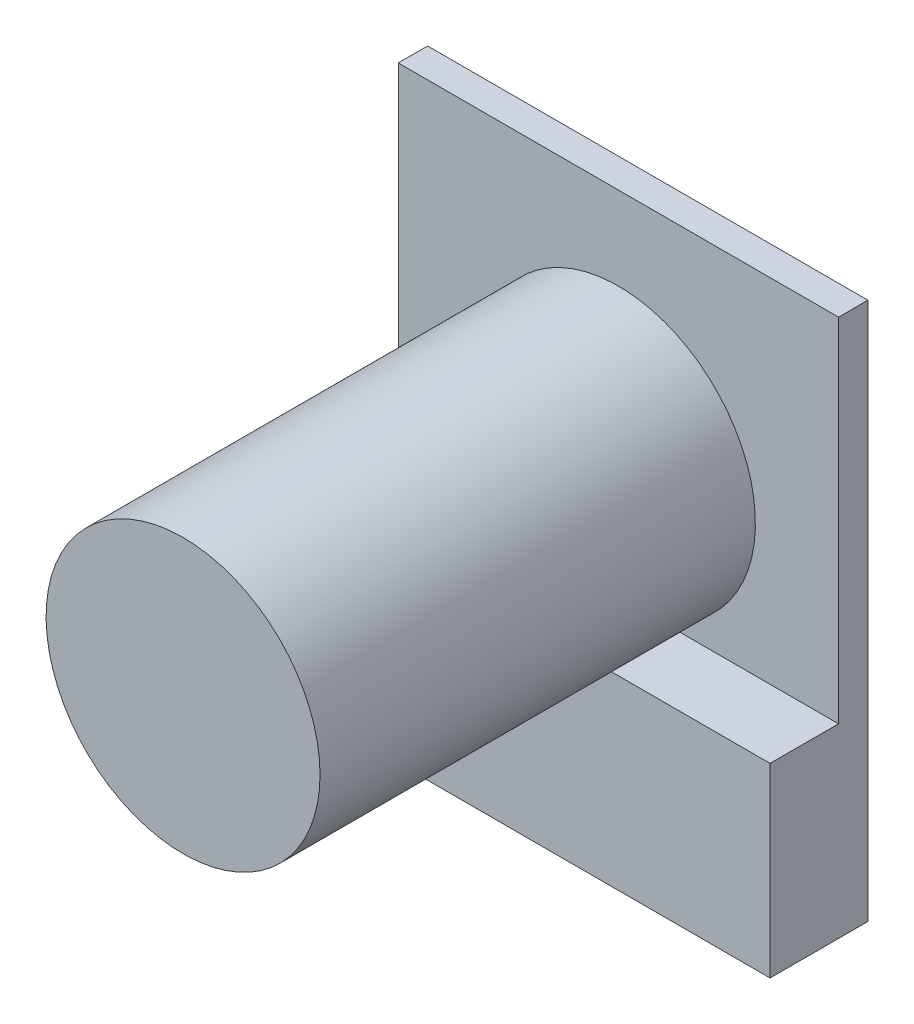
SolidWorks part; units mm, degrees
ref_plane "前视基准面" through (0, 0, 0) normal (0, 0, 1) x (1, 0, 0)
ref_plane "上视基准面" through (0, 0, 0) normal (0, 1, 0) x (1, 0, 0)
ref_plane "右视基准面" through (0, 0, 0) normal (1, 0, 0) x (0, 0, -1)
other "Configuration Table"
sketch "草图1" plane through (0, 0, 0) normal (0, 0, 1) x (1, 0, 0)
  line L0 (-45, -45) -> (45, -45)
  line L1 (45, -45) -> (45, 45)
  line L2 (45, 45) -> (-45, 45)
  line L3 (-45, 45) -> (-45, -45)
extrude "凸台-拉伸1" add sketch "草图1" along normal blind 6 flip side to cut
sketch "草图2" plane through (0, 0, 0) normal (0, 0, 1) x (1, 0, 0)
  circle A0 centre (0, 0) radius 28
extrude "凸台-拉伸2" add sketch "草图2" along normal blind 95 flip side to cut
sketch "草图3" plane through (0, 0, 0) normal (0, 0, 1) x (1, 0, 0)
  line L0 (-45, -65) -> (45, -65)
  line L1 (45, -65) -> (45, -27)
  line L2 (45, -45) -> (45, 45) construction
  line L3 (45, -27) -> (-45, -27)
  line L4 (-45, 45) -> (-45, -45) construction
  line L5 (-45, -27) -> (-45, -65)
extrude "凸台-拉伸3" add sketch "草图3" along normal blind 20 flip side to cut
